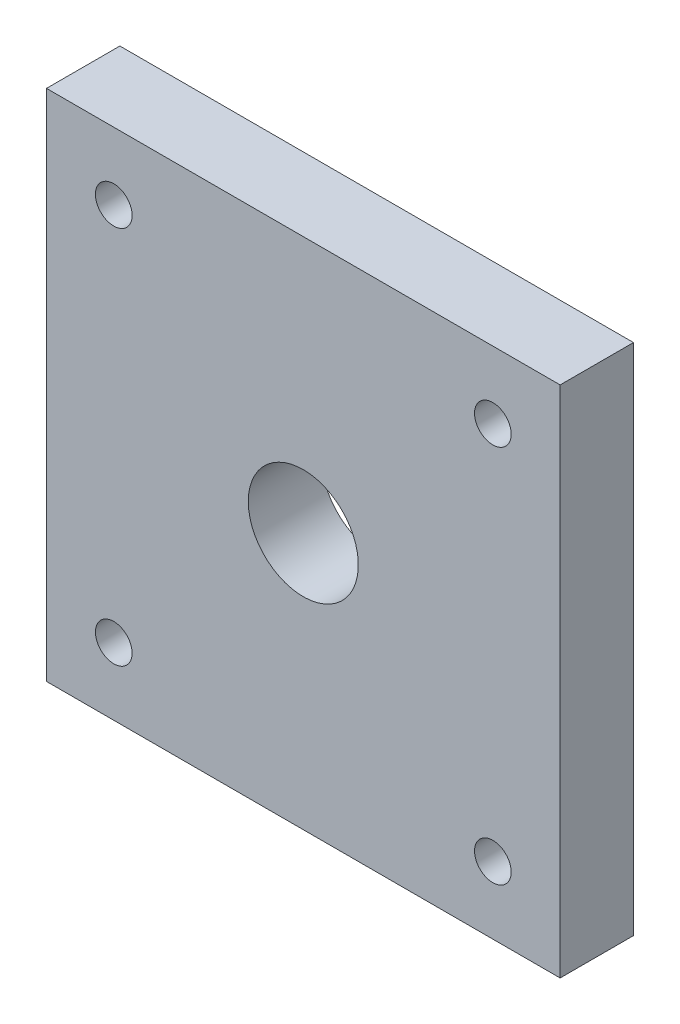
SolidWorks part; units mm, degrees
ref_plane "前视基准面" through (0, 0, 0) normal (0, 0, 1) x (1, 0, 0)
ref_plane "上视基准面" through (0, 0, 0) normal (0, 1, 0) x (1, 0, 0)
ref_plane "右视基准面" through (0, 0, 0) normal (1, 0, 0) x (0, 0, -1)
sketch "草图1" plane through (0, 0, 0) normal (0, 0, 1) x (1, 0, 0)
  line L1 (-21, 21) -> (21, 21)
  line L2 (-21, 21) -> (-21, -21)
  line L3 (-21, -21) -> (21, -21)
  line L4 (21, 21) -> (21, -21)
  line L5 (-21, 21) -> (21, -21) construction
  line L6 (-21, -21) -> (21, 21) construction
  point P0 (0, 0)
  dimension "D1" = 42
extrude "凸台-拉伸1" add sketch "草图1" along normal blind 6
sketch "草图2" plane through (0, 0, 0) normal (0, 0, -1) x (-1, 0, 0)
  line L0 (-21, 21) -> (21, -21)
  line L1 (21, 21) -> (-21, -21)
  circle A0 centre (-15.5, 15.5) radius 1.5
  circle A1 centre (15.5, 15.5) radius 1.5
  circle A2 centre (15.5, -15.5) radius 1.5
  circle A3 centre (-15.5, -15.5) radius 1.5
  point P16 (0, 0)
  point P17 (0, 0)
  point P18 (0, 0)
  point P19 (0, 0)
  dimension "D1" = 3
  dimension "D2" = 31
extrude "切除-拉伸1" cut sketch "草图2" against normal through all contours A0 | A1 | A2 | A3
sketch "草图3" plane through (0, 0, 0) normal (0, 0, -1) x (-1, 0, 0)
  circle A0 centre (0, 0) radius 4.5
  dimension "D1" = 9
extrude "切除-拉伸2" cut sketch "草图3" against normal through all
